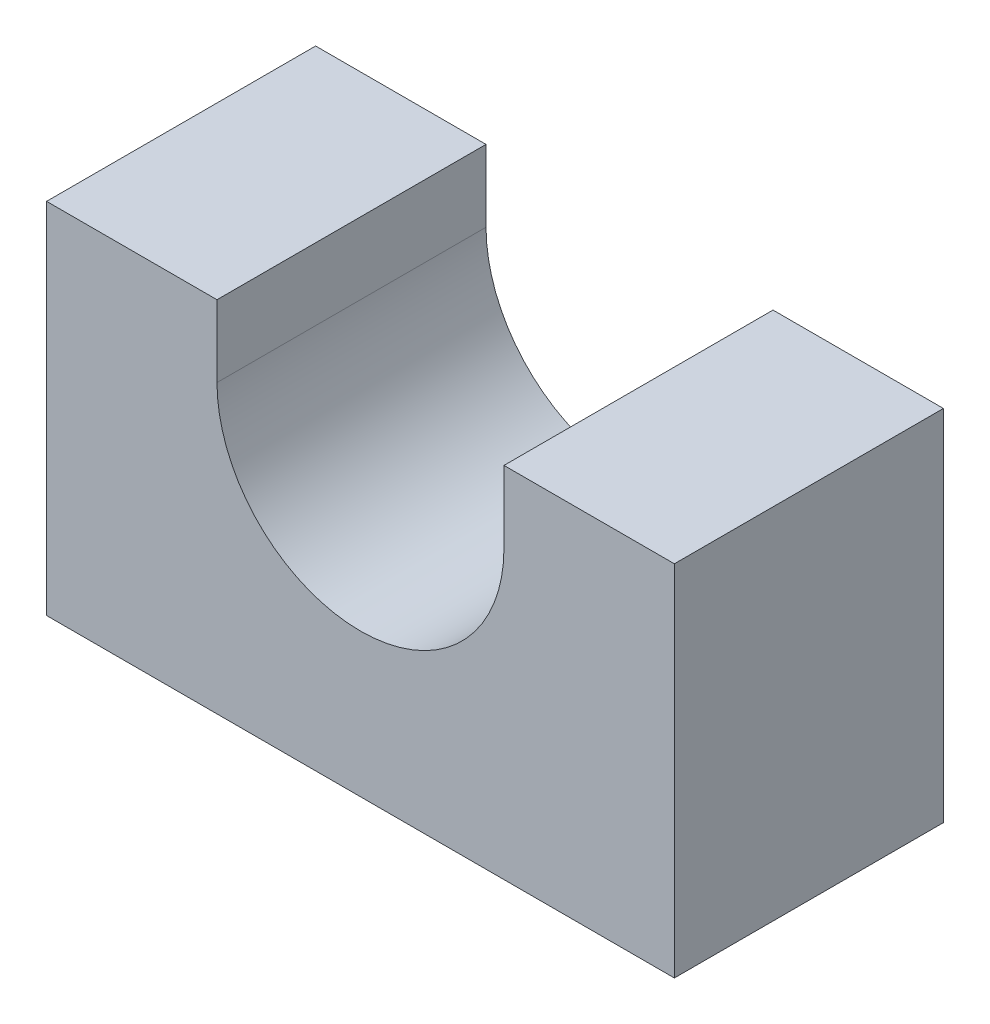
SolidWorks part; units mm, degrees
material "Plain Carbon Steel"
ref_plane "Front Plane" through (0, 0, 0) normal (0, 0, 1) x (1, 0, 0)
ref_plane "Top Plane" through (0, 0, 0) normal (0, 1, 0) x (1, 0, 0)
ref_plane "Right Plane" through (0, 0, 0) normal (1, 0, 0) x (0, 0, -1)
sketch "Sketch3" plane through (0, 0, 0) normal (0, 0, 1) x (1, 0, 0)
  line L0 (-175, 0) -> (175, 0)
  line L1 (-175, 0) -> (-175, 200)
  line L2 (175, 0) -> (175, 200)
  line L3 (-175, 200) -> (-80, 200)
  line L4 (175, 200) -> (80, 200)
  line L5 (-80, 200) -> (-80, 160)
  line L6 (80, 200) -> (80, 160)
  arc A0 (-80, 160) -> (80, 160) centre (0, 160) ccw
  dimension "D4" = 80
  dimension "D1" = 350
  dimension "D2" = 200
  dimension "D3" = 40
extrude "Boss-Extrude1" add sketch "Sketch3" along normal blind 150
